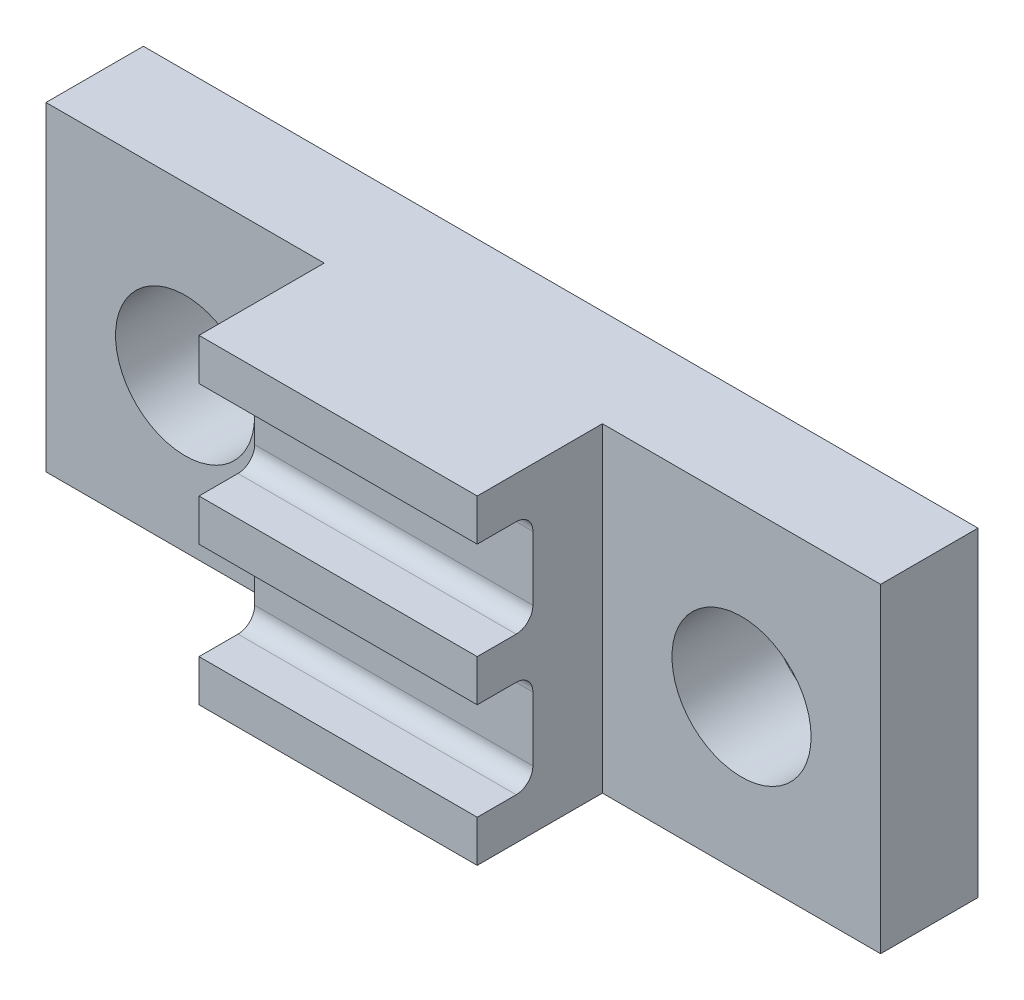
SolidWorks part; units mm, degrees
ref_plane "Front Plane" through (0, 0, 0) normal (0, 0, 1) x (1, 0, 0)
ref_plane "Top Plane" through (0, 0, 0) normal (0, 1, 0) x (1, 0, 0)
ref_plane "Right Plane" through (0, 0, 0) normal (1, 0, 0) x (0, 0, -1)
sketch "Sketch1" plane through (0, 0, 0) normal (0, 0, 1) x (1, 0, 0)
  line L1 (-15, 5.75) -> (15, 5.75)
  line L2 (-15, 5.75) -> (-15, -5.75)
  line L3 (-15, -5.75) -> (15, -5.75)
  line L4 (15, 5.75) -> (15, -5.75)
  line L5 (-15, 5.75) -> (15, -5.75) construction
  line L6 (-15, -5.75) -> (15, 5.75) construction
  circle A0 centre (-10, -0.25) radius 2.5
  circle A1 centre (10, -0.25) radius 2.5
  point P0 (0, 0)
  dimension "D3" = 5
  dimension "D6" = 5
  dimension "D1" = 30
  dimension "D2" = 11.5
  dimension "D4" = 5
  dimension "D5" = 5
extrude "Boss-Extrude1" add sketch "Sketch1" along normal blind 3.5
sketch "Sketch2" plane through (0, 0, 3.5) normal (0, 0, 1) x (1, 0, 0)
  line L1 (-15, -5.75) -> (15, -5.75) construction
  line L2 (-5, 5.75) -> (5, 5.75)
  line L3 (-5, 5.75) -> (-5, -5.75)
  line L4 (-5, -5.75) -> (5, -5.75)
  line L5 (5, 5.75) -> (5, -5.75)
  line L6 (-5, 5.75) -> (5, -5.75) construction
  line L7 (-5, -5.75) -> (5, 5.75) construction
  point P0 (0, 0)
  dimension "D1" = 10
extrude "Boss-Extrude2" add sketch "Sketch2" along normal blind 4.5
sketch "Sketch3" plane through (-5, 0, 0) normal (-1, 0, 0) x (0, 0, 1)
  line L0 (8, 5.75) -> (8, -5.75) construction
  line L1 (6, 4.25) -> (8, 4.25)
  line L2 (6, 4.25) -> (6, 0.75)
  line L3 (6, 0.75) -> (8, 0.75)
  line L4 (8, 4.25) -> (8, 0.75)
  line L5 (6, 4.25) -> (8, 0.75) construction
  line L6 (6, 0.75) -> (8, 4.25) construction
  line L7 (8, 5.75) -> (3.5, 5.75) construction
  point P0 (7, 2.5)
  dimension "D1" = 3.5
  dimension "D2" = 1.5
  dimension "D3" = 2
extrude "Cut-Extrude1" cut sketch "Sketch3" against normal through all
fillet "Fillet1" radius 0.6 2 edges at (0, 0.75, 6) (0, 4.25, 6)
pattern_linear "LPattern1" count 2 spacing 5 along (0, -1, 0) of "Cut-Extrude1", "Fillet1"
